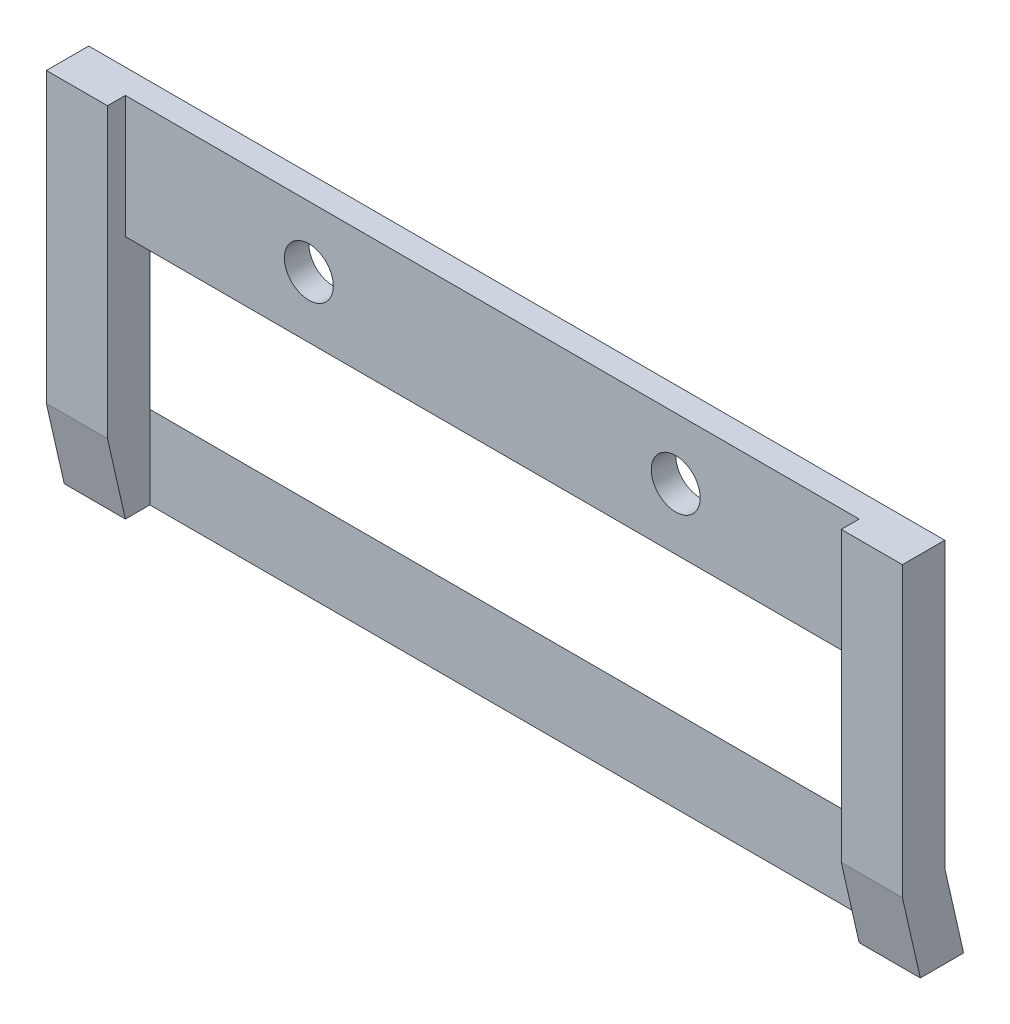
SolidWorks part; units mm, degrees
ref_plane "前视基准面" through (0, 0, 0) normal (0, 0, 1) x (1, 0, 0)
ref_plane "上视基准面" through (0, 0, 0) normal (0, 1, 0) x (1, 0, 0)
ref_plane "右视基准面" through (0, 0, 0) normal (1, 0, 0) x (0, 0, -1)
sketch "草图1" plane through (0, 0, 0) normal (0, 0, 1) x (1, 0, 0)
  line L0 (-44.7549, 0) -> (15.2451, 0)
  line L2 (15.2451, 10) -> (-44.7549, 10)
  line L4 (-44.7549, 10) -> (-49.7549, 10)
  line L5 (-49.7549, 10) -> (-49.7549, -20)
  line L6 (-49.7549, -20) -> (-44.7549, -20)
  line L7 (-44.7549, -20) -> (-44.7549, 0)
  line L8 (15.2451, 10) -> (20.2451, 10)
  line L9 (20.2451, 10) -> (20.2451, -20)
  line L10 (20.2451, -20) -> (15.2451, -20)
  line L11 (15.2451, -20) -> (15.2451, 0)
  dimension "D1" = 60
  dimension "D2" = 10
  dimension "D3" = 5
  dimension "D4" = 5
  dimension "D5" = 30
  dimension "D6" = 30
  dimension "D7" = 10
extrude "凸台-拉伸1" add sketch "草图1" along normal blind 2
sketch "草图2" plane through (-49.7549, 0, 0) normal (-1, 0, 0) x (0, 0, 1)
  line L0 (0, 10) -> (0, -20)
  line L1 (0, -20) -> (2, -20)
  line L2 (2, -20) -> (3.4612, -13.5779)
  line L3 (3.4612, -13.5779) -> (3.4612, 10)
  line L4 (3.4612, 10) -> (0, 10)
extrude "凸台-拉伸2" add sketch "草图2" against normal up to surface (5 mm away) up to face at (-44.7549, -10, 1)
ref_plane "基准面1" through (-14.7549, 0, 0) normal (-1, 0, 0) x (0, 0, 1)
sketch "草图3" plane through (20.2451, 0, 0) normal (1, 0, 0) x (0, 0, -1)
  line L0 (-3.4612, 10) -> (0, 10) construction
  line L1 (-3.4612, 10) -> (0, 10)
  line L2 (-3.4612, -13.5779) -> (-3.4612, 10) construction
  line L3 (-2, -20) -> (0, -20) construction
  line L4 (0, -20) -> (0, 10)
  line L5 (0, 10) -> (-2, 10)
  line L6 (-2, 10) -> (-2, -20)
  line L7 (-2, -20) -> (0, -20)
  line L8 (0, -20) -> (0, 10)
  line L9 (0, 10) -> (-2, 10)
  line L11 (-2, -20) -> (0, -20)
  line L12 (-2, -20) -> (-3.4612, -13.5779) construction
  line L13 (0, 10) -> (0, -20) construction
  line L14 (-3.4612, 10) -> (0, 10)
  line L15 (-3.4612, -13.5779) -> (-3.4612, 10)
  line L16 (-2, -20) -> (0, -20)
  line L17 (-2, -20) -> (-3.4612, -13.5779)
  line L18 (0, 10) -> (0, -20)
  line M7 (-2, 10) -> (-2, -20)
  dimension "D1" = 0
extrude "凸台-拉伸3" add sketch "草图3" against normal up to surface (5 mm away) contours L17 L1 L15 M7 up to face at (15.2451, -10, 1)
sketch "草图4" plane through (0, 0, 2) normal (0, 0, 1) x (1, 0, 0)
  line L1 (15.2451, 10) -> (-44.7549, 10) construction
  line L2 (-14.7549, 1.9036) -> (-14.7549, -1.9036) construction
  circle A0 centre (-29.7549, 5) radius 2
  dimension "D1" = 4
  dimension "D2" = 5
  dimension "D3" = 15
extrude "切除-拉伸1" cut sketch "草图4" against normal blind 10 contours A0
mirror "镜向2" about plane through (-14.7549, 0, 0) normal (-1, 0, 0) of "切除-拉伸1"
sketch "草图5" plane through (-49.7549, 0, 0) normal (-1, 0, 0) x (0, 0, 1)
  line L0 (0, -13.2254) -> (-1.5414, -20)
  line L1 (0, 10) -> (0, -20) construction
  line L2 (-1.5414, -20) -> (0, -20)
  line L3 (0, -20) -> (0, -13.2254)
  line L4 (2, -20) -> (3.4612, -13.5779) construction
extrude "凸台-拉伸4" add sketch "草图5" against normal up to surface (65 mm away)
mirror "镜向3" about plane through (-14.7549, 0, 0) normal (-1, 0, 0) of "凸台-拉伸4"
